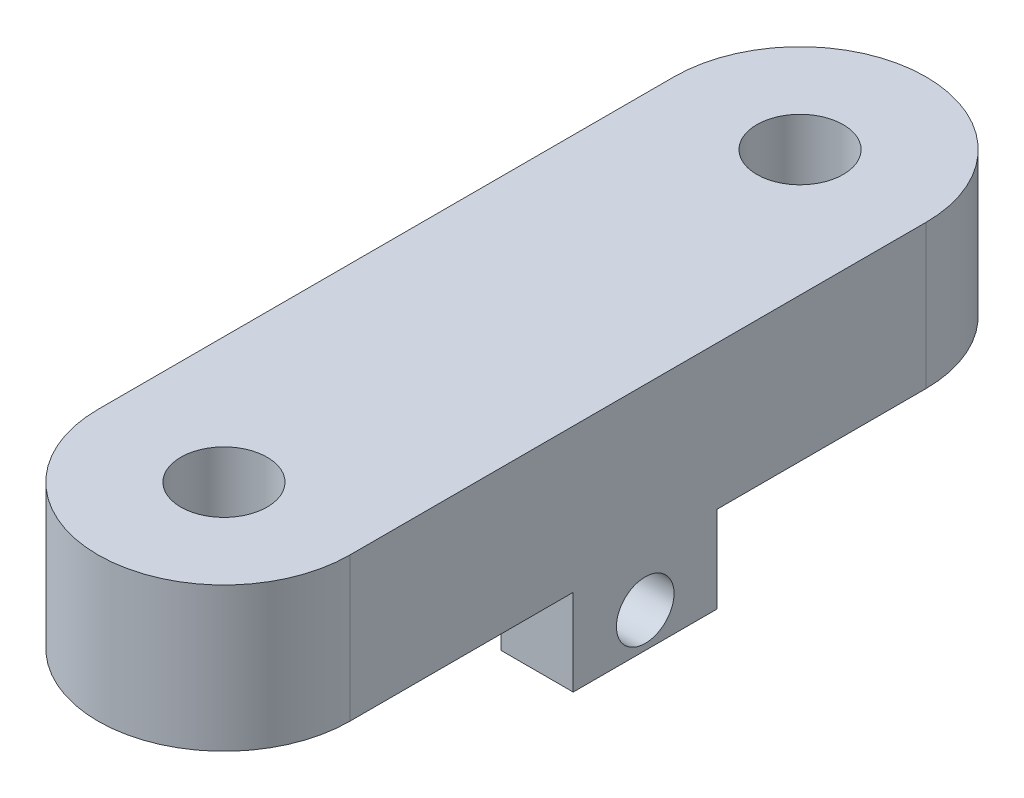
SolidWorks part; units mm, degrees
ref_plane "Front Plane" through (0, 0, 0) normal (0, 0, 1) x (1, 0, 0)
ref_plane "Top Plane" through (0, 0, 0) normal (0, 1, 0) x (1, 0, 0)
ref_plane "Right Plane" through (0, 0, 0) normal (1, 0, 0) x (0, 0, -1)
sketch "Sketch1" plane through (0, 0, 0) normal (0, 1, 0) x (1, 0, 0)
  line L0 (-12.5, 0) -> (-12.5, 10)
  line L1 (-12.5, 10) -> (-17.5, 10)
  line L2 (-17.5, 0) -> (-12.5, 0)
  line L3 (-17.5, 10) -> (-17.5, 0)
  line L4 (-5, 10) -> (0, 10)
  line L5 (-5, 10) -> (-5, 0)
  line L6 (-5, 0) -> (0, 0)
  line L7 (0, 10) -> (0, 0)
  dimension "D1" = 5
  dimension "D2" = 5
  dimension "D3" = 7.5
  dimension "D4" = 10
extrude "Boss-Extrude1" add sketch "Sketch1" along normal blind 6
sketch "Sketch2" plane through (0, 0, 0) normal (1, 0, 0) x (0, 0, -1)
  line L0 (0, 6) -> (0, 0) construction
  line L1 (0, 0) -> (10, 0) construction
  circle A0 centre (5, 2.43) radius 2
  dimension "D1" = 4
  dimension "D2" = 5
  dimension "D3" = 2.43
extrude "Cut-Extrude1" cut sketch "Sketch2" against normal blind 100
sketch "Sketch4" plane through (0, 6, 0) normal (0, 1, 0) x (1, 0, 0)
  line L0 (-17.5, -15.5) -> (-17.5, 24.5)
  line L3 (0, -15.5) -> (0, 24.5)
  line L4 (-17.5, 10) -> (-17.5, 0) construction
  arc A0 (-17.5, 24.5) -> (0, 24.5) centre (-8.75, 24.5) cw
  arc A1 (-17.5, -15.5) -> (0, -15.5) centre (-8.75, -15.5) ccw
  circle A2 centre (-8.75, 24.5) radius 3
  circle A3 centre (-8.75, -15.5) radius 3
  point P3 (-17.5, 4.5)
  point P6 (0, 4.5)
  point P14 (-8.75, 33.25)
  dimension "D2" = 6
  dimension "D3" = 20
  dimension "D4" = 20
  dimension "D1" = 20
extrude "Boss-Extrude2" add sketch "Sketch4" along normal blind 10
